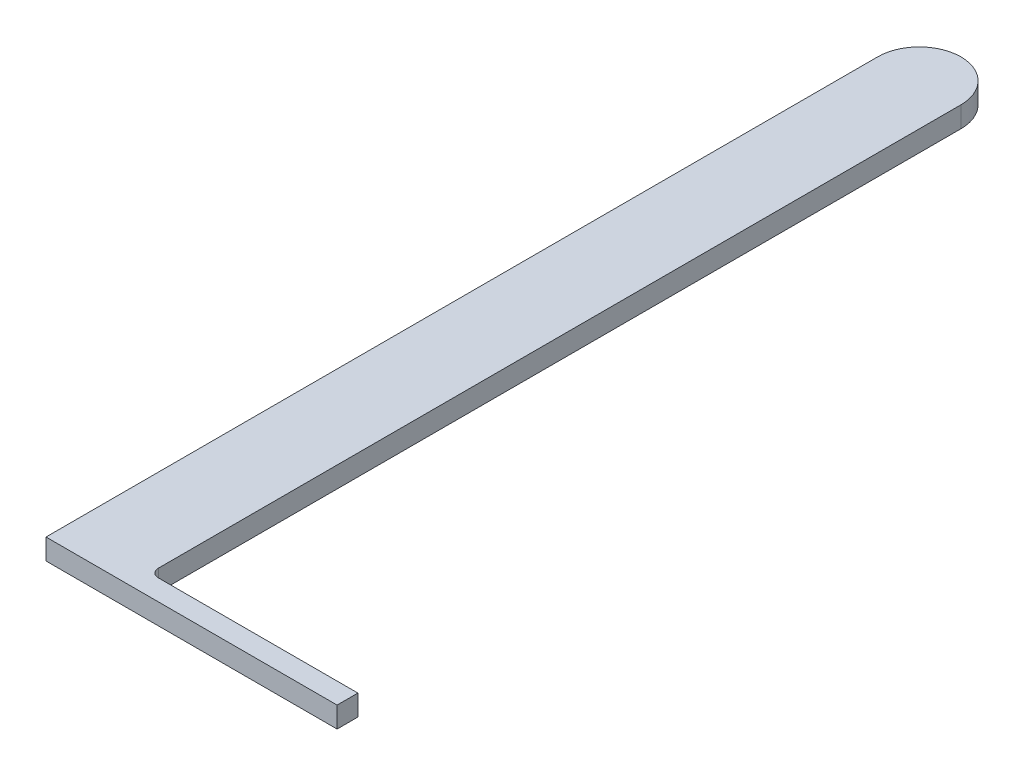
SolidWorks part; units mm, degrees
ref_plane "Front Plane" through (0, 0, 0) normal (0, 0, 1) x (1, 0, 0)
ref_plane "Top Plane" through (0, 0, 0) normal (0, 1, 0) x (1, 0, 0)
ref_plane "Right Plane" through (0, 0, 0) normal (1, 0, 0) x (0, 0, -1)
sketch "Sketch1" plane through (0, 0, 0) normal (0, 1, 0) x (1, 0, 0)
  line L1 (-12.7, 0) -> (12.7, 0)
  line L2 (-12.7, 0) -> (-12.7, -247.65)
  line L3 (-12.7, -247.65) -> (12.7, -247.65)
  line L4 (12.7, 0) -> (12.7, -247.65)
  circle A0 centre (0, 0) radius 12.7
  dimension "D1" = 25.4
  dimension "D2" = 247.65
extrude "Boss-Extrude1" add sketch "Sketch1" along normal blind 6.35 contours A0 L2 L3 L4 | L1 A0 | L1 A0
sketch "Sketch2" plane through (0, 6.35, 0) normal (0, 1, 0) x (1, 0, 0)
  line L1 (-12.7, -247.65) -> (76.2, -247.65)
  line L2 (-12.7, -247.65) -> (-12.7, -254)
  line L3 (-12.7, -254) -> (76.2, -254)
  line L4 (76.2, -247.65) -> (76.2, -254)
  dimension "D1" = 88.9
  dimension "D2" = 6.35
extrude "Boss-Extrude2" add sketch "Sketch2" against normal up to surface (6.35 mm away) up to face at (0, 0, 120.65)
fillet "Fillet1" radius 2.54 1 edges
